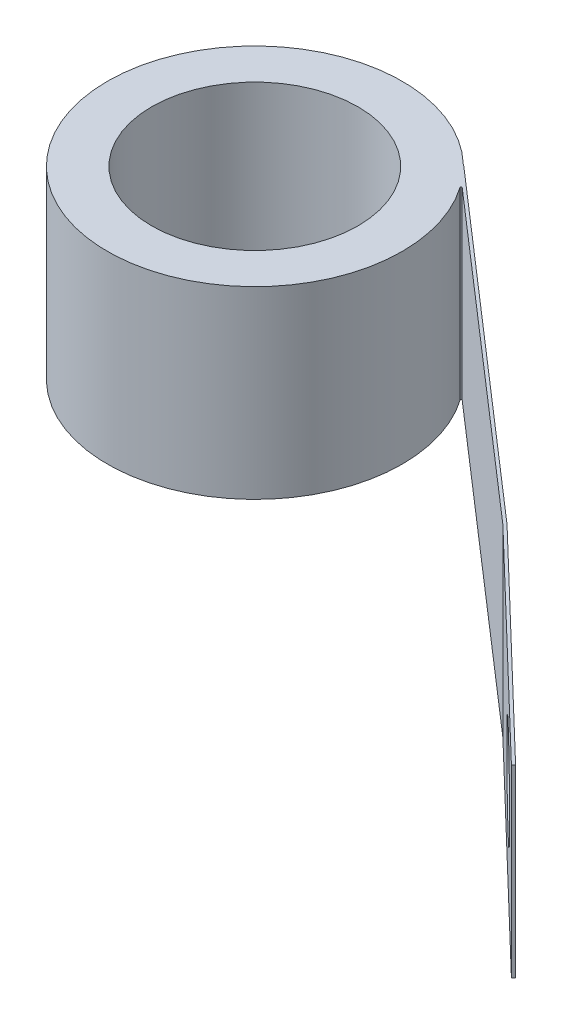
SolidWorks part; units mm, degrees
ref_plane "Front Plane" through (0, 0, 0) normal (0, 0, 1) x (1, 0, 0)
ref_plane "Top Plane" through (0, 0, 0) normal (0, 1, 0) x (1, 0, 0)
ref_plane "Right Plane" through (0, 0, 0) normal (1, 0, 0) x (0, 0, -1)
sketch "Sketch1" plane through (0, 0, 0) normal (0, 1, 0) x (1, 0, 0)
  line L0 (15.0352, -6.3438) -> (3.3337, 3.8331)
  line L1 (14.9649, -6.4171) -> (4.0294, 3.0936)
  line L2 (0, 0) -> (8.531, 8.888) construction
  line L3 (22.2948, -13.4525) -> (14.9649, -6.4171)
  line L4 (15.9965, -7.4073) -> (22.6384, -13.7823) construction
  line L5 (22.3651, -13.3792) -> (15.0352, -6.3438)
  line L6 (22.3651, -13.3792) -> (22.2948, -13.4525)
  circle A0 centre (0, 0) radius 3.556
  circle A1 centre (0, 0) radius 5.08
  dimension "D1" = 7.112
  dimension "D2" = 10.16
  dimension "D3" = 15.24
  dimension "D4" = 0.1016
  dimension "D5" = 10.16
extrude "Boss-Extrude1" add sketch "Sketch1" along normal blind 6.35 contours A1 A0 | A1 L1 L3 L6 L5 L0
sketch "Sketch2" plane through (3.3055, 0, -4.9148) normal (0.6925, 0, -0.7214) x (-0.7214, 0, -0.6925)
  line L1 (-26.4186, 6.35) -> (-26.4186, 0) construction
  circle A0 centre (-22.6086, 3.175) radius 1.651
  point P2 (-26.4186, 3.175)
  dimension "D1" = 3.302
  dimension "D2" = 3.81
extrude "Cut-Extrude1" cut sketch "Sketch2" against normal blind 6.35
fillet "Fillet1" radius 0.0254 1 edges at (4.0294, 3.175, -3.0936)
